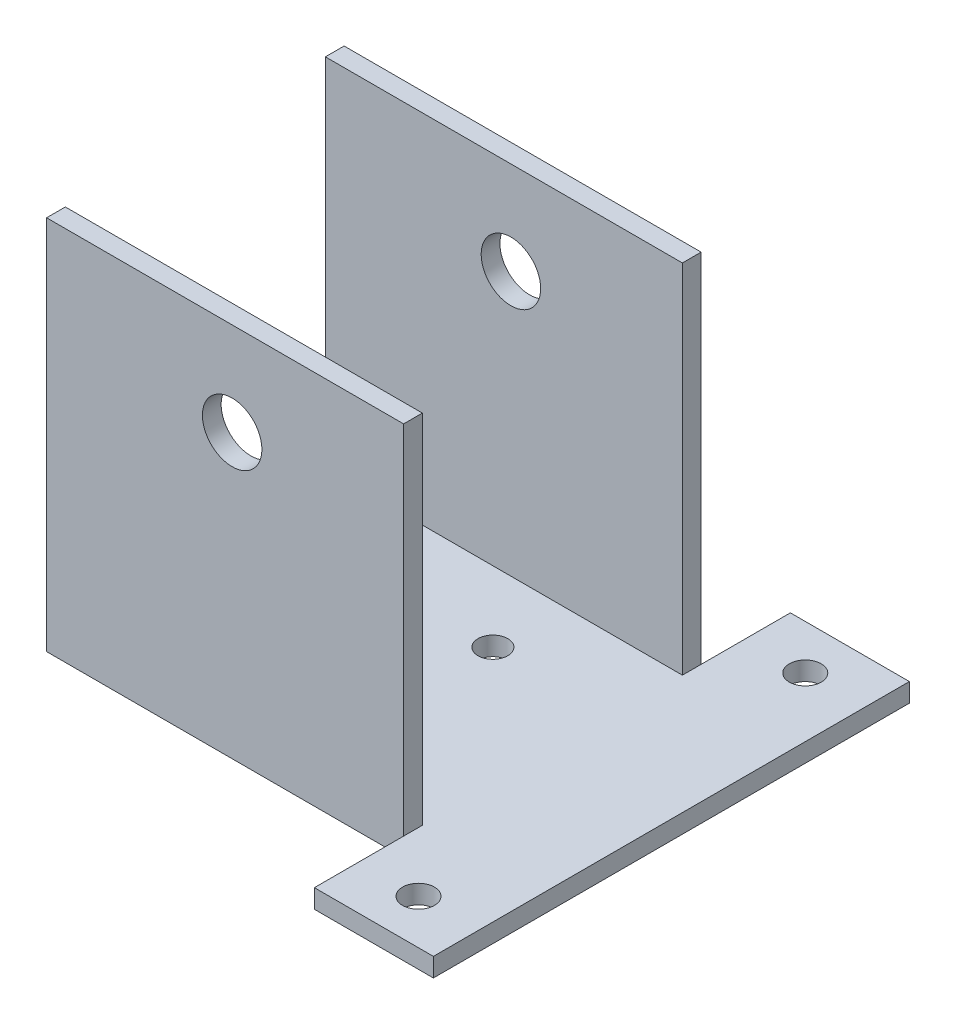
SolidWorks part; units mm, degrees
ref_plane "Front Plane" through (0, 0, 0) normal (0, 0, 1) x (1, 0, 0)
ref_plane "Top Plane" through (0, 0, 0) normal (0, 1, 0) x (1, 0, 0)
ref_plane "Right Plane" through (0, 0, 0) normal (1, 0, 0) x (0, 0, -1)
sketch "Sketch1" plane through (0, 0, 0) normal (0, 1, 0) x (1, 0, 0)
  line L0 (-25.4, 15.875) -> (12.7, 15.875)
  line L1 (12.7, 15.875) -> (12.7, 25.4)
  line L2 (12.7, 25.4) -> (25.4, 25.4)
  line L3 (25.4, 25.4) -> (25.4, -25.4)
  line L4 (25.4, -25.4) -> (12.7, -25.4)
  line L5 (12.7, -25.4) -> (12.7, -15.875)
  line L6 (12.7, -15.875) -> (-25.4, -15.875)
  line L7 (-25.4, -15.875) -> (-25.4, 15.875)
  line L8 (19.05, 20.6375) -> (19.05, -20.6375) construction
  line L9 (0, 6.35) -> (0, -6.35) construction
  circle A0 centre (19.05, 20.6375) radius 1.7
  circle A1 centre (19.05, -20.6375) radius 1.7
  circle A2 centre (0, 6.35) radius 1.5875
  circle A3 centre (0, -6.35) radius 1.5875
  point P18 (0, 0)
  dimension "D5" = 3.4
  dimension "D9" = 3.175
  dimension "D1" = 50.8
  dimension "D2" = 50.8
  dimension "D3" = 12.7
  dimension "D4" = 9.525
  dimension "D6" = 41.275
  dimension "D7" = 6.35
  dimension "D8" = 25.4
  dimension "D10" = 12.7
  dimension "D11" = 9.525
  dimension "D12" = 4.7625
  dimension "D13" = 31.75
extrude "Boss-Extrude1" add sketch "Sketch1" along normal blind 2
sketch "Sketch2" plane through (0, 2, 0) normal (0, 1, 0) x (1, 0, 0)
  line L1 (-25.4, 15.875) -> (12.7, 15.875)
  line L2 (-25.4, 15.875) -> (-25.4, 13.875)
  line L3 (-25.4, 13.875) -> (12.7, 13.875)
  line L4 (12.7, 15.875) -> (12.7, 13.875)
  line L5 (-25.4, -15.875) -> (12.7, -15.875)
  line L6 (-25.4, -15.875) -> (-25.4, -13.875)
  line L7 (-25.4, -13.875) -> (12.7, -13.875)
  line L8 (12.7, -15.875) -> (12.7, -13.875)
  dimension "D1" = 2
  dimension "D2" = 2
extrude "Boss-Extrude2" add sketch "Sketch2" along normal blind 38.1
sketch "Sketch3" plane through (0, 0, 15.875) normal (0, 0, 1) x (1, 0, 0)
  line L1 (12.7, 2) -> (25.4, 2) construction
  line L2 (-25.4, 40.1) -> (-25.4, 0) construction
  circle A0 centre (-5.6, 30.168) radius 3.175
  point P6 (0, 0)
  dimension "D1" = 6.35
  dimension "D2" = 28.168
  dimension "D3" = 19.8
extrude "Cut-Extrude1" cut sketch "Sketch3" against normal through all
